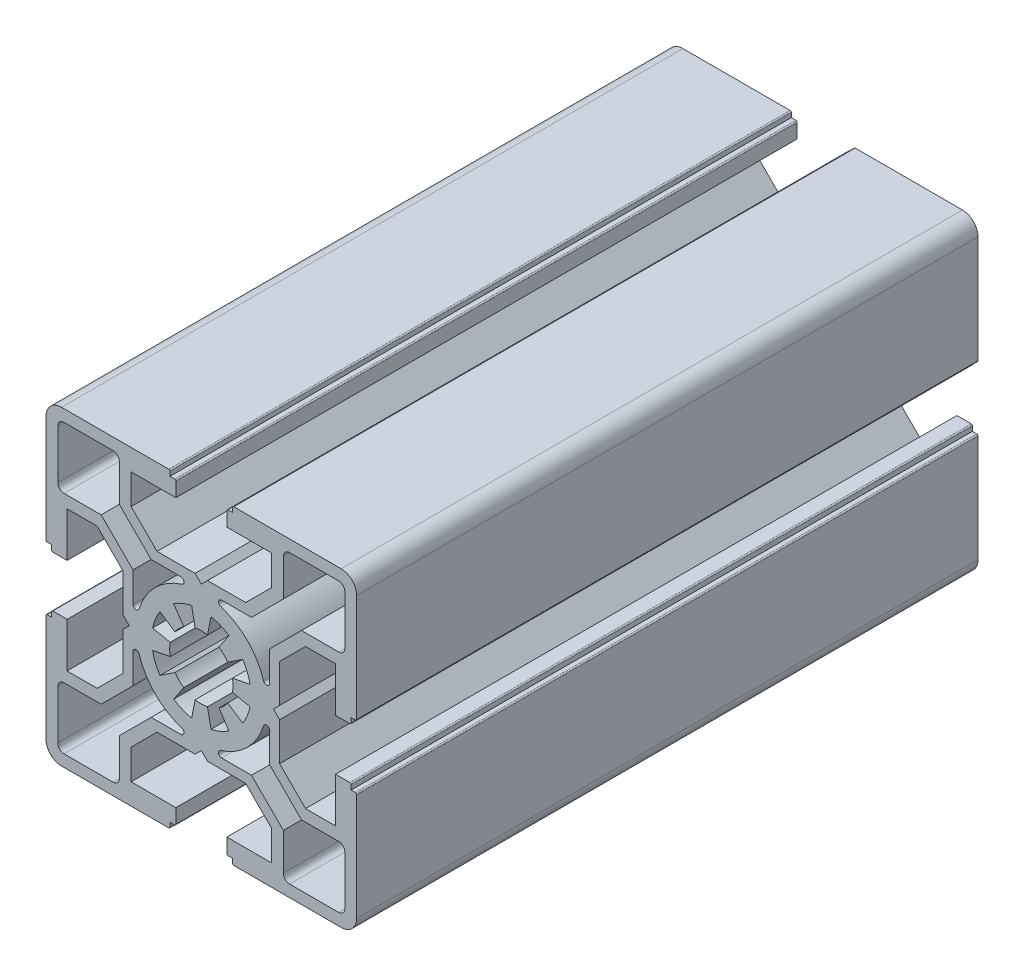
SolidWorks part; units mm, degrees
ref_plane "前视基准面" through (0, 0, 0) normal (0, 0, 1) x (1, 0, 0)
ref_plane "上视基准面" through (0, 0, 0) normal (0, 1, 0) x (1, 0, 0)
ref_plane "右视基准面" through (0, 0, 0) normal (1, 0, 0) x (0, 0, -1)
sketch "草图1" plane through (0, 0, 0) normal (0, 0, 1) x (1, 0, 0)
  line B0 (-5.25, 25) -> (-22.5, 25)
  line B1 (-25, 22.5) -> (-25, 5.25)
  line B2 (-24.8, 5.05) -> (-24.1, 5.05)
  line B3 (-24.1, 5.05) -> (-24.1, 4.3)
  line B4 (-23.9, 4.1) -> (-21.6, 4.1)
  line B5 (-21.6, 4.1) -> (-21.6, 11.3)
  line B6 (-21.6, 11.3) -> (-16.7698, 11.3)
  line B7 (-16.7698, 11.3) -> (-12.6, 7.1302)
  line B8 (-12.6, 7.1302) -> (-12.6, 1)
  line B9 (-12.6, 1) -> (-11.6, 0)
  line B10 (-11.6, 0) -> (-12.6, -1)
  line B11 (-12.6, -1) -> (-12.6, -7.1302)
  line B12 (-12.6, -7.1302) -> (-16.7698, -11.3)
  line B13 (-16.7698, -11.3) -> (-21.6, -11.3)
  line B14 (-21.6, -11.3) -> (-21.6, -4.1)
  line B15 (-21.6, -4.1) -> (-23.9, -4.1)
  line B16 (-24.1, -4.3) -> (-24.1, -5.05)
  line B17 (-24.1, -5.05) -> (-24.8, -5.05)
  line B18 (-25, -5.25) -> (-25, -22.5)
  line B19 (-22.5, -25) -> (-5.25, -25)
  line B20 (-5.05, -24.8) -> (-5.05, -24.1)
  line B21 (-5.05, -24.1) -> (-4.3, -24.1)
  line B22 (-4.1, -23.9) -> (-4.1, -21.6)
  line B23 (-4.1, -21.6) -> (-11.3, -21.6)
  line B24 (-11.3, -21.6) -> (-11.3, -16.7698)
  line B25 (-11.3, -16.7698) -> (-7.1302, -12.6)
  line B26 (-7.1302, -12.6) -> (-1, -12.6)
  line B27 (-1, -12.6) -> (0, -11.6)
  line B28 (0, -11.6) -> (1, -12.6)
  line B29 (1, -12.6) -> (7.1302, -12.6)
  line B30 (7.1302, -12.6) -> (11.3, -16.7698)
  line B31 (11.3, -16.7698) -> (11.3, -21.6)
  line B32 (11.3, -21.6) -> (4.1, -21.6)
  line B33 (4.1, -21.6) -> (4.1, -23.9)
  line B34 (4.3, -24.1) -> (5.05, -24.1)
  line B35 (5.05, -24.1) -> (5.05, -24.8)
  line B36 (5.25, -25) -> (22.5, -25)
  line B37 (25, -22.5) -> (25, -5.25)
  line B38 (24.8, -5.05) -> (24.1, -5.05)
  line B39 (24.1, -5.05) -> (24.1, -4.3)
  line B40 (23.9, -4.1) -> (21.6, -4.1)
  line B41 (21.6, -4.1) -> (21.6, -11.3)
  line B42 (21.6, -11.3) -> (16.7698, -11.3)
  line B43 (16.7698, -11.3) -> (12.6, -7.1302)
  line B44 (12.6, -7.1302) -> (12.6, -1)
  line B45 (12.6, -1) -> (11.6, 0)
  line B46 (11.6, 0) -> (12.6, 1)
  line B47 (12.6, 1) -> (12.6, 7.1302)
  line B48 (12.6, 7.1302) -> (16.7698, 11.3)
  line B49 (16.7698, 11.3) -> (21.6, 11.3)
  line B50 (21.6, 11.3) -> (21.6, 4.1)
  line B51 (21.6, 4.1) -> (23.9, 4.1)
  line B52 (24.1, 4.3) -> (24.1, 5.05)
  line B53 (24.1, 5.05) -> (24.8, 5.05)
  line B54 (25, 5.25) -> (25, 22.5)
  line B55 (22.5, 25) -> (5.25, 25)
  line B56 (5.05, 24.8) -> (5.05, 24.1)
  line B57 (5.05, 24.1) -> (4.3, 24.1)
  line B58 (4.1, 23.9) -> (4.1, 21.6)
  line B59 (4.1, 21.6) -> (11.3, 21.6)
  line B60 (11.3, 21.6) -> (11.3, 16.7698)
  line B61 (11.3, 16.7698) -> (7.1302, 12.6)
  line B62 (7.1302, 12.6) -> (1, 12.6)
  line B63 (1, 12.6) -> (0, 11.6)
  line B64 (0, 11.6) -> (-1, 12.6)
  line B65 (-1, 12.6) -> (-7.1302, 12.6)
  line B66 (-7.1302, 12.6) -> (-11.3, 16.7698)
  line B67 (-11.3, 16.7698) -> (-11.3, 21.6)
  line B68 (-11.3, 21.6) -> (-4.1, 21.6)
  line B69 (-4.1, 21.6) -> (-4.1, 23.9)
  line B70 (-4.3, 24.1) -> (-5.05, 24.1)
  line B71 (-5.05, 24.1) -> (-5.05, 24.8)
  line B72 (2.8334, 4.2405) -> (4.4446, 6.6518)
  line B73 (1.5607, 7.8463) -> (0.995, 5.002)
  line B74 (-0.995, 5.002) -> (-1.5607, 7.8463)
  line B75 (-4.4446, 6.6518) -> (-2.8334, 4.2405)
  line B76 (-4.2405, 2.8334) -> (-6.6518, 4.4446)
  line B77 (-7.8463, 1.5607) -> (-5.002, 0.995)
  line B78 (-5.002, -0.995) -> (-7.8463, -1.5607)
  line B79 (-6.6518, -4.4446) -> (-4.2405, -2.8334)
  line B80 (-2.8334, -4.2405) -> (-4.4446, -6.6518)
  line B81 (-1.5607, -7.8463) -> (-0.995, -5.002)
  line B82 (0.995, -5.002) -> (1.5607, -7.8463)
  line B83 (4.4446, -6.6518) -> (2.8334, -4.2405)
  line B84 (4.2405, -2.8334) -> (6.6518, -4.4446)
  line B85 (7.8463, -1.5607) -> (5.002, -0.995)
  line B86 (5.002, 0.995) -> (7.8463, 1.5607)
  line B87 (6.6518, 4.4446) -> (4.2405, 2.8334)
  line B88 (3.2787, -11) -> (8.0757, -11)
  line B89 (8.0757, -11) -> (13.2, -16.1243)
  line B90 (13.2, -16.1243) -> (13.2, -22.1)
  line B91 (14.2, -23.1) -> (22.1, -23.1)
  line B92 (23.1, -22.1) -> (23.1, -14.2)
  line B93 (22.1, -13.2) -> (16.1243, -13.2)
  line B94 (16.1243, -13.2) -> (11, -8.0757)
  line B95 (11, -8.0757) -> (11, -3.2787)
  line B96 (-8.0757, 11) -> (-13.2, 16.1243)
  line B97 (-13.2, 16.1243) -> (-13.2, 22.1)
  line B98 (-14.2, 23.1) -> (-22.1, 23.1)
  line B99 (-23.1, 22.1) -> (-23.1, 14.2)
  line B100 (-22.1, 13.2) -> (-16.1243, 13.2)
  line B101 (-16.1243, 13.2) -> (-11, 8.0757)
  line B102 (-11, 8.0757) -> (-11, 3.2787)
  line B103 (-3.2787, 11) -> (-8.0757, 11)
  line B104 (13.2, 22.1) -> (13.2, 16.1243)
  line B105 (13.2, 16.1243) -> (8.0757, 11)
  line B106 (8.0757, 11) -> (3.2787, 11)
  line B107 (11, 3.2787) -> (11, 8.0757)
  line B108 (11, 8.0757) -> (16.1243, 13.2)
  line B109 (16.1243, 13.2) -> (22.1, 13.2)
  line B110 (23.1, 14.2) -> (23.1, 22.1)
  line B111 (22.1, 23.1) -> (14.2, 23.1)
  line B112 (-16.1243, -13.2) -> (-22.1, -13.2)
  line B113 (-23.1, -14.2) -> (-23.1, -22.1)
  line B114 (-22.1, -23.1) -> (-14.2, -23.1)
  line B115 (-13.2, -22.1) -> (-13.2, -16.1243)
  line B116 (-13.2, -16.1243) -> (-8.0757, -11)
  line B117 (-8.0757, -11) -> (-3.2787, -11)
  line B118 (-11, -3.2787) -> (-11, -8.0757)
  line B119 (-11, -8.0757) -> (-16.1243, -13.2)
  arc B120 (-22.5, 25) -> (-25, 22.5) centre (-22.5, 22.5) ccw
  arc B121 (-25, 5.25) -> (-24.8, 5.05) centre (-24.8, 5.25) ccw
  arc B122 (-24.1, 4.3) -> (-23.9, 4.1) centre (-23.9, 4.3) ccw
  arc B123 (-23.9, -4.1) -> (-24.1, -4.3) centre (-23.9, -4.3) ccw
  arc B124 (-24.8, -5.05) -> (-25, -5.25) centre (-24.8, -5.25) ccw
  arc B125 (-25, -22.5) -> (-22.5, -25) centre (-22.5, -22.5) ccw
  arc B126 (-5.25, -25) -> (-5.05, -24.8) centre (-5.25, -24.8) ccw
  arc B127 (-4.3, -24.1) -> (-4.1, -23.9) centre (-4.3, -23.9) ccw
  arc B128 (4.1, -23.9) -> (4.3, -24.1) centre (4.3, -23.9) ccw
  arc B129 (5.05, -24.8) -> (5.25, -25) centre (5.25, -24.8) ccw
  arc B130 (22.5, -25) -> (25, -22.5) centre (22.5, -22.5) ccw
  arc B131 (25, -5.25) -> (24.8, -5.05) centre (24.8, -5.25) ccw
  arc B132 (24.1, -4.3) -> (23.9, -4.1) centre (23.9, -4.3) ccw
  arc B133 (23.9, 4.1) -> (24.1, 4.3) centre (23.9, 4.3) ccw
  arc B134 (24.8, 5.05) -> (25, 5.25) centre (24.8, 5.25) ccw
  arc B135 (25, 22.5) -> (22.5, 25) centre (22.5, 22.5) ccw
  arc B136 (5.25, 25) -> (5.05, 24.8) centre (5.25, 24.8) ccw
  arc B137 (4.3, 24.1) -> (4.1, 23.9) centre (4.3, 23.9) ccw
  arc B138 (-4.1, 23.9) -> (-4.3, 24.1) centre (-4.3, 23.9) ccw
  arc B139 (-5.05, 24.8) -> (-5.25, 25) centre (-5.25, 24.8) ccw
  arc B140 (4.2405, 2.8334) -> (2.8334, 4.2405) centre (0, 0) ccw
  arc B141 (4.4446, 6.6518) -> (1.5607, 7.8463) centre (0, 0) ccw
  arc B142 (0.995, 5.002) -> (-0.995, 5.002) centre (0, 0) ccw
  arc B143 (-1.5607, 7.8463) -> (-4.4446, 6.6518) centre (0, 0) ccw
  arc B144 (-2.8334, 4.2405) -> (-4.2405, 2.8334) centre (0, 0) ccw
  arc B145 (-6.6518, 4.4446) -> (-7.8463, 1.5607) centre (0, 0) ccw
  arc B146 (-5.002, 0.995) -> (-5.002, -0.995) centre (0, 0) ccw
  arc B147 (-7.8463, -1.5607) -> (-6.6518, -4.4446) centre (0, 0) ccw
  arc B148 (-4.2405, -2.8334) -> (-2.8334, -4.2405) centre (0, 0) ccw
  arc B149 (-4.4446, -6.6518) -> (-1.5607, -7.8463) centre (0, 0) ccw
  arc B150 (-0.995, -5.002) -> (0.995, -5.002) centre (0, 0) ccw
  arc B151 (1.5607, -7.8463) -> (4.4446, -6.6518) centre (0, 0) ccw
  arc B152 (2.8334, -4.2405) -> (4.2405, -2.8334) centre (0, 0) ccw
  arc B153 (6.6518, -4.4446) -> (7.8463, -1.5607) centre (0, 0) ccw
  arc B154 (5.002, -0.995) -> (5.002, 0.995) centre (0, 0) ccw
  arc B155 (7.8463, 1.5607) -> (6.6518, 4.4446) centre (0, 0) ccw
  arc B156 (3.1297, -10.0227) -> (10.0227, -3.1297) centre (0, 0) ccw
  arc B157 (3.1297, -10.0227) -> (3.2787, -11) centre (3.2787, -10.5) ccw
  arc B158 (13.2, -22.1) -> (14.2, -23.1) centre (14.2, -22.1) ccw
  arc B159 (22.1, -23.1) -> (23.1, -22.1) centre (22.1, -22.1) ccw
  arc B160 (23.1, -14.2) -> (22.1, -13.2) centre (22.1, -14.2) ccw
  arc B161 (11, -3.2787) -> (10.0227, -3.1297) centre (10.5, -3.2787) ccw
  arc B162 (-13.2, 22.1) -> (-14.2, 23.1) centre (-14.2, 22.1) ccw
  arc B163 (-22.1, 23.1) -> (-23.1, 22.1) centre (-22.1, 22.1) ccw
  arc B164 (-23.1, 14.2) -> (-22.1, 13.2) centre (-22.1, 14.2) ccw
  arc B165 (-11, 3.2787) -> (-10.0227, 3.1297) centre (-10.5, 3.2787) ccw
  arc B166 (-3.1297, 10.0227) -> (-10.0227, 3.1297) centre (0, 0) ccw
  arc B167 (-3.1297, 10.0227) -> (-3.2787, 11) centre (-3.2787, 10.5) ccw
  arc B168 (14.2, 23.1) -> (13.2, 22.1) centre (14.2, 22.1) ccw
  arc B169 (3.2787, 11) -> (3.1297, 10.0227) centre (3.2787, 10.5) ccw
  arc B170 (10.0227, 3.1297) -> (3.1297, 10.0227) centre (0, 0) ccw
  arc B171 (10.0227, 3.1297) -> (11, 3.2787) centre (10.5, 3.2787) ccw
  arc B172 (22.1, 13.2) -> (23.1, 14.2) centre (22.1, 14.2) ccw
  arc B173 (23.1, 22.1) -> (22.1, 23.1) centre (22.1, 22.1) ccw
  arc B174 (-22.1, -13.2) -> (-23.1, -14.2) centre (-22.1, -14.2) ccw
  arc B175 (-23.1, -22.1) -> (-22.1, -23.1) centre (-22.1, -22.1) ccw
  arc B176 (-14.2, -23.1) -> (-13.2, -22.1) centre (-14.2, -22.1) ccw
  arc B177 (-3.2787, -11) -> (-3.1297, -10.0227) centre (-3.2787, -10.5) ccw
  arc B178 (-10.0227, -3.1297) -> (-3.1297, -10.0227) centre (0, 0) ccw
  arc B179 (-10.0227, -3.1297) -> (-11, -3.2787) centre (-10.5, -3.2787) ccw
sketch_block_instance "A$C398A0CE3-1"
sketch_block "A$C398A0CE3"
extrude "凸台-拉伸1" add sketch "草图1" along normal blind 100
